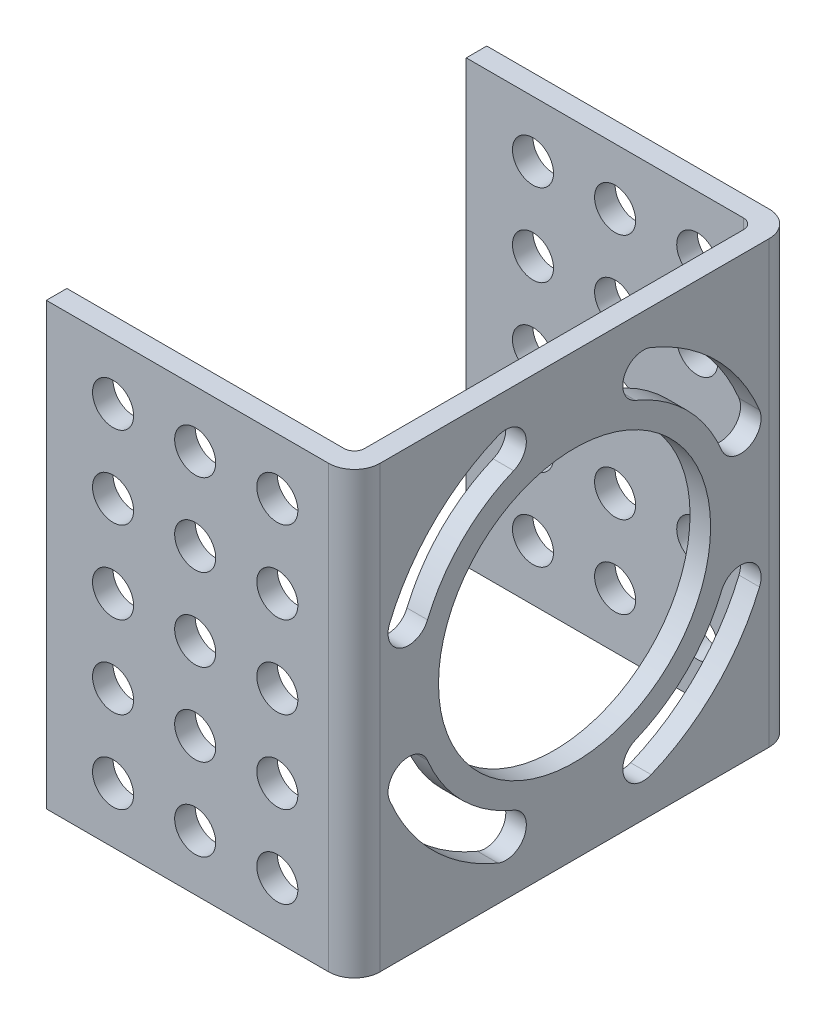
SolidWorks part; units mm, degrees
material "AISI 304"
ref_plane "前视基准面" through (0, 0, 0) normal (0, 0, 1) x (1, 0, 0)
ref_plane "上视基准面" through (0, 0, 0) normal (0, 1, 0) x (1, 0, 0)
ref_plane "右视基准面" through (0, 0, 0) normal (1, 0, 0) x (0, 0, -1)
sketch "Sketch1" plane through (0, 0, 0) normal (1, 0, 0) x (0, 0, -1)
  line L0 (0, 0) -> (42.9, 0)
  line L1 (42.9, 0) -> (42.9, -42.9)
  line L2 (42.9, -42.9) -> (0, -42.9)
  line L3 (0, -42.9) -> (0, 0)
  dimension "D1" = 42.9
  dimension "D2" = 42.9
extrude "Boss-Extrude1" add sketch "Sketch1" along normal blind 2
sketch "Sketch3" plane through (0, 0, 0) normal (-1, 0, 0) x (0, 0, 1)
  line L0 (-42.9, 0) -> (0, -42.9) construction
  line L1 (0, 0) -> (-42.9, -42.9) construction
  line L2 (-21.45, 0.7758) -> (-21.45, -45.0686) construction
  line L3 (-21.45, -21.45) -> (-31.2588, 2.2305) construction
  line L4 (-21.45, -21.45) -> (-11.6412, 2.2305) construction
  circle A0 centre (-21.45, -21.45) radius 13.25
  arc A5 (-39.4657, -13.9877) -> (-35.7701, -15.5184) centre (-37.6179, -14.753) ccw
  arc A6 (-27.3816, -7.1299) -> (-28.9123, -3.4343) centre (-28.147, -5.2821) ccw
  arc A7 (-28.9123, -3.4343) -> (-39.4657, -13.9877) centre (-21.45, -21.45) ccw
  arc A8 (-13.9877, -3.4343) -> (-15.5184, -7.1299) centre (-14.753, -5.2821) ccw
  arc A9 (-7.1299, -15.5184) -> (-15.5184, -7.1299) centre (-21.45, -21.45) ccw
  arc A10 (-27.3816, -7.1299) -> (-35.7701, -15.5184) centre (-21.45, -21.45) ccw
  arc A11 (-7.1299, -15.5184) -> (-3.4343, -13.9877) centre (-5.2821, -14.753) ccw
  arc A12 (-3.4343, -13.9877) -> (-13.9877, -3.4343) centre (-21.45, -21.45) ccw
  arc A13 (-3.4343, -28.9123) -> (-7.1299, -27.3816) centre (-5.2821, -28.147) ccw
  arc A14 (-15.5184, -35.7701) -> (-7.1299, -27.3816) centre (-21.45, -21.45) ccw
  arc A15 (-15.5184, -35.7701) -> (-13.9877, -39.4657) centre (-14.753, -37.6179) ccw
  arc A16 (-13.9877, -39.4657) -> (-3.4343, -28.9123) centre (-21.45, -21.45) ccw
  arc A17 (-28.9123, -39.4657) -> (-27.3816, -35.7701) centre (-28.147, -37.6179) ccw
  arc A18 (-35.7701, -27.3816) -> (-27.3816, -35.7701) centre (-21.45, -21.45) ccw
  arc A19 (-35.7701, -27.3816) -> (-39.4657, -28.9123) centre (-37.6179, -28.147) ccw
  arc A20 (-39.4657, -28.9123) -> (-28.9123, -39.4657) centre (-21.45, -21.45) ccw
  point P16 (-5.95, -21.45)
  point P23 (-1.95, -21.45)
  point P46 (-21.45, -21.45)
  dimension "D1" = 26.5
  dimension "D6" = 2
  dimension "D7" = 2
  dimension "D4" = 19.5
  dimension "D5" = 15.5
  dimension "D3" = 22.5
  dimension "D8" = 4
extrude "Cut-Extrude2" cut sketch "Sketch3" against normal through all
sketch "Sketch4" plane through (0, 0, 0) normal (-1, 0, 0) x (0, 0, 1)
  line L0 (-42.9, 0) -> (-40.9, 0)
  line L1 (-42.9, 0) -> (0, 0) construction
  line L2 (-40.9, 0) -> (-40.9, -42.9)
  line L3 (0, -42.9) -> (-42.9, -42.9) construction
  line L4 (-40.9, -42.9) -> (-42.9, -42.9)
  line L5 (-42.9, -42.9) -> (-42.9, 0)
  line L6 (0, 0) -> (0, -42.9)
  line L7 (0, -42.9) -> (-2, -42.9)
  line L8 (-2, -42.9) -> (-2, 0)
  line L9 (-2, 0) -> (0, 0)
  dimension "D1" = 2
  dimension "D2" = 2
extrude "Boss-Extrude2" add sketch "Sketch4" along normal blind 43
sketch "Sketch5" plane through (0, 0, -42.9) normal (0, 0, -1) x (-1, 0, 0)
  line L0 (0, 2.2846) -> (0, -44.643) construction
  line L1 (0, 0) -> (43, -42.9) construction
  line L2 (43, 0) -> (0, -42.9) construction
  line L3 (21.5, 0.6597) -> (21.5, -45.1459) construction
  line L4 (5.5, 0.6597) -> (5.5, -45.1459) construction
  line L5 (28, 0) -> (28, -42.9)
  line L6 (-2, 0) -> (43, 0) construction
  line L7 (-2, -42.9) -> (43, -42.9) construction
  line L8 (28, -42.9) -> (43, -42.9)
  line L9 (43, -42.9) -> (43, 0)
  line L10 (43, 0) -> (28, 0)
  circle A1 centre (5.5, -5.4872) radius 2
  circle A2 centre (13.5, -5.4872) radius 2
  circle A3 centre (21.5, -5.4872) radius 2
  circle A4 centre (13.5, -13.4872) radius 2
  circle A5 centre (21.5, -13.4872) radius 2
  circle A6 centre (13.5, -21.4872) radius 2
  circle A7 centre (21.5, -21.4872) radius 2
  circle A8 centre (13.5, -29.4872) radius 2
  circle A9 centre (21.5, -29.4872) radius 2
  circle A10 centre (13.5, -37.4872) radius 2
  circle A11 centre (21.5, -37.4872) radius 2
  circle A12 centre (5.5, -13.4872) radius 2
  circle A13 centre (5.5, -21.4872) radius 2
  circle A14 centre (5.5, -29.4872) radius 2
  circle A15 centre (5.5, -37.4872) radius 2
  dimension "D1" = 15
  dimension "D3" = 4
  dimension "D2" = 16
  dimension "D4" = 3
  dimension "D5" = 5
extrude "Cut-Extrude4" cut sketch "Sketch5" against normal through all
fillet "Fillet1" radius 2.5 2 edges at (2, -21.45, 0) (2, -21.45, -42.9)
fillet "Fillet2" radius 1 2 edges at (0, -21.45, -2) (0, -21.45, -40.9)
